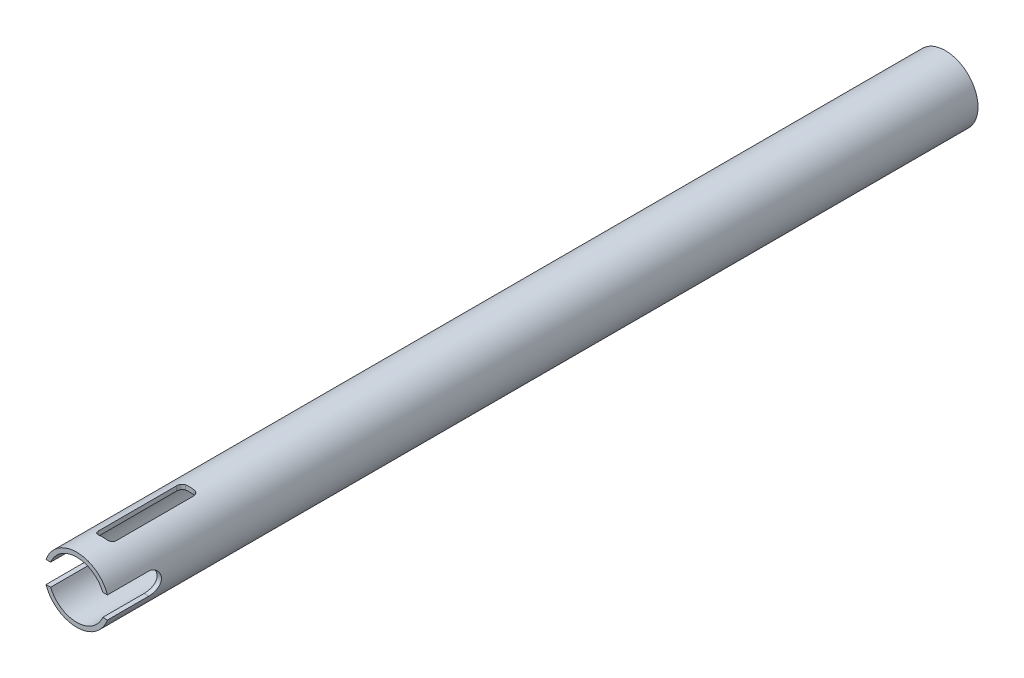
SolidWorks part; units mm, degrees
ref_plane "Front Plane" through (0, 0, 0) normal (0, 0, 1) x (1, 0, 0)
ref_plane "Top Plane" through (0, 0, 0) normal (0, 1, 0) x (1, 0, 0)
ref_plane "Right Plane" through (0, 0, 0) normal (1, 0, 0) x (0, 0, -1)
sketch "Sketch1" plane through (0, 0, 0) normal (0, 0, 1) x (1, 0, 0)
  circle A0 centre (0, 0) radius 4.7625
  circle A1 centre (0, 0) radius 4.1275
  dimension "D1" = 9.525
  dimension "D2" = 8.255
extrude "ShaftBody" add sketch "Sketch1" against normal blind 127
sketch "Sketch6" plane through (0, 0, 0) normal (1, 0, 0) x (0, 0, -1)
  line L1 (6.0325, 1.5875) -> (0, 1.5875)
  line L2 (6.0325, 1.5875) -> (6.0325, -1.5875) construction
  line L3 (6.0325, -1.5875) -> (0, -1.5875)
  line L4 (0, 1.5875) -> (0, -1.5875)
  arc A0 (6.0325, -1.5875) -> (6.0325, 1.5875) centre (6.0325, 0) ccw
  dimension "D1" = 3.175
  dimension "D2" = 6.0325
extrude "SideCuts" cut sketch "Sketch6" against normal through all and the other way through all
sketch "Sketch7" plane through (0, 0, 0) normal (0, 1, 0) x (1, 0, 0)
  line L0 (-4.4901, 0) -> (4.4901, 0) construction
  line L1 (-0.635, 3.81) -> (0.635, 3.81)
  line L2 (-1.27, 4.445) -> (-1.27, 15.875)
  line L3 (-0.635, 16.51) -> (0.635, 16.51)
  line L4 (1.27, 4.445) -> (1.27, 15.875)
  line L5 (-1.27, 3.81) -> (1.27, 16.51) construction
  line L6 (-1.27, 16.51) -> (1.27, 3.81) construction
  arc A0 (0.635, 3.81) -> (1.27, 4.445) centre (0.635, 4.445) ccw
  arc A1 (-0.635, 3.81) -> (-1.27, 4.445) centre (-0.635, 4.445) cw
  arc A2 (1.27, 15.875) -> (0.635, 16.51) centre (0.635, 15.875) ccw
  arc A3 (-0.635, 16.51) -> (-1.27, 15.875) centre (-0.635, 15.875) ccw
  point P0 (0, 10.16)
  dimension "D4" = 0.635
  dimension "D1" = 2.54
  dimension "D2" = 3.81
  dimension "D3" = 12.7
extrude "Cut-Extrude2" cut sketch "Sketch7" along normal up to next
